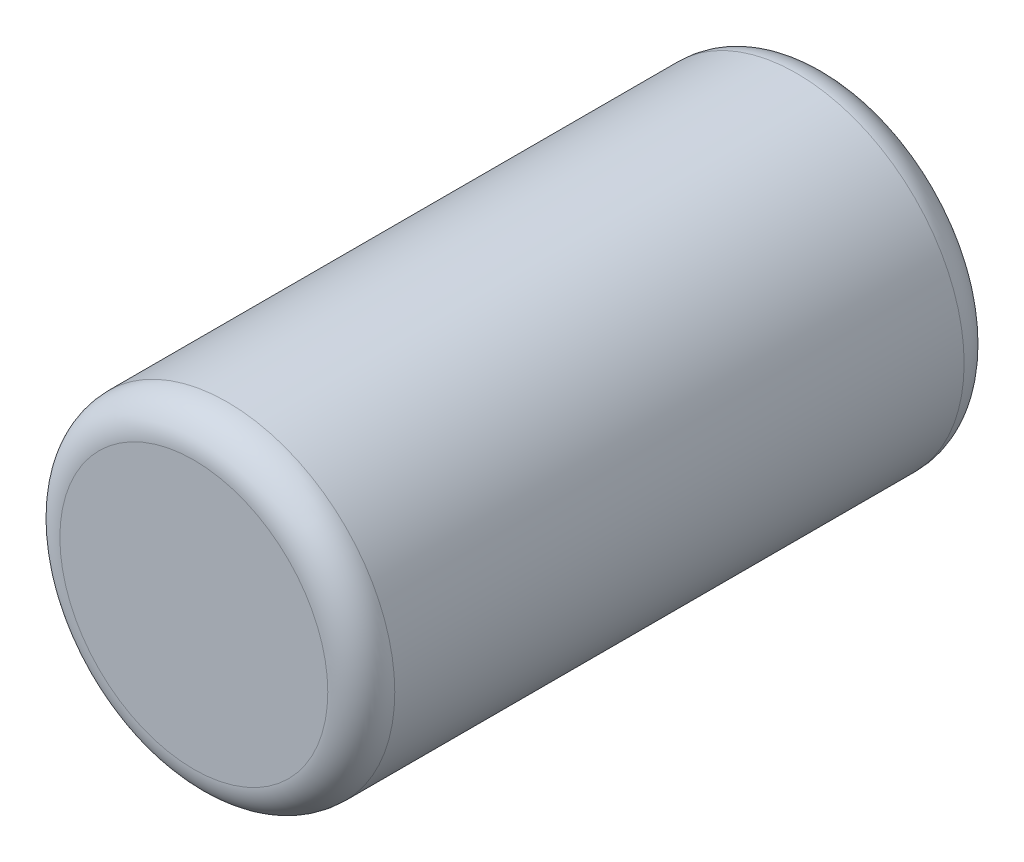
SolidWorks part; units mm, degrees
ref_plane "Front Plane" through (0, 0, 0) normal (0, 0, 1) x (1, 0, 0)
ref_plane "Top Plane" through (0, 0, 0) normal (0, 1, 0) x (1, 0, 0)
ref_plane "Right Plane" through (0, 0, 0) normal (1, 0, 0) x (0, 0, -1)
sketch "Sketch1" plane through (0, 0, 0) normal (0, 0, 1) x (1, 0, 0)
  circle A0 centre (0, 0) radius 5
  dimension "D1" = 10
extrude "Boss-Extrude1" add sketch "Sketch1" along normal mid plane 19
fillet "Fillet1" radius 1 2 edges at (5, 0, -9.5) (5, 0, 9.5)
